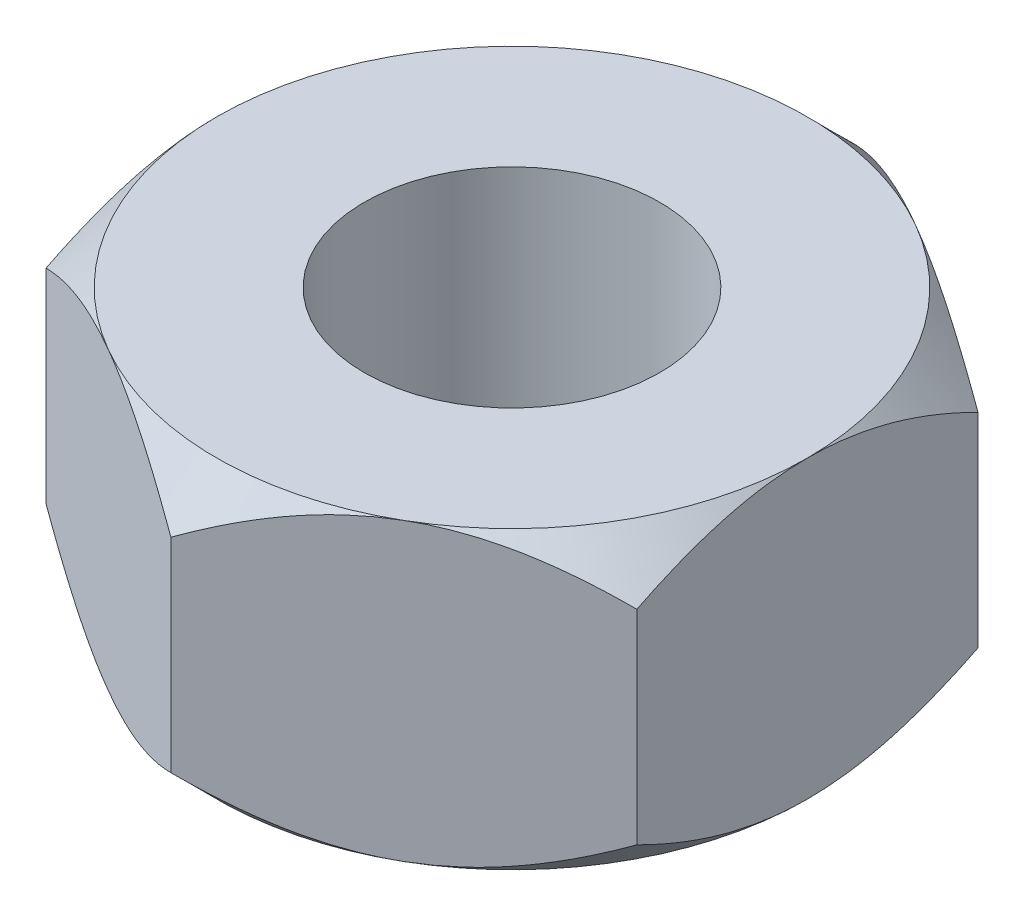
SolidWorks part; units mm, degrees
material "Plain Carbon Steel"
ref_plane "Front Plane" through (0, 0, 0) normal (0, 0, 1) x (1, 0, 0)
ref_plane "Top Plane" through (0, 0, 0) normal (0, 1, 0) x (1, 0, 0)
ref_plane "Right Plane" through (0, 0, 0) normal (1, 0, 0) x (0, 0, -1)
sketch "Sketch1" plane through (0, 0, 0) normal (0, 1, 0) x (1, 0, 0)
  line L1 (0, 4.6188) -> (-4, 2.3094)
  line L2 (-4, 2.3094) -> (-4, -2.3094)
  line L3 (-4, -2.3094) -> (0, -4.6188)
  line L4 (0, -4.6188) -> (4, -2.3094)
  line L5 (4, -2.3094) -> (4, 2.3094)
  line L6 (4, 2.3094) -> (0, 4.6188)
  circle A0 centre (0, 0) radius 2
  circle A1 centre (0, 0) radius 4 construction
  dimension "D1" = 4
  dimension "D2" = 8
extrude "Boss-Extrude1" add sketch "Sketch1" along normal mid plane 4
sketch "Sketch2" plane through (0, 2, 0) normal (0, 1, 0) x (1, 0, 0)
  line L0 (-4, 2.3094) -> (-4, -2.3094) construction
  circle A0 centre (0, 0) radius 4
sketch "Sketch3" plane through (0, 0, 0) normal (0, 0, 1) x (1, 0, 0)
  line L0 (-4.65, 1.35) -> (-4, 2)
  line L3 (-4, 2) -> (-4.65, 2)
  line L4 (-4.65, 2) -> (-4.65, 1.35)
  dimension "D1" = 0.65
  dimension "D2" = 0.65
sweep "Cut-Sweep1" cut profiles "Sketch3" path "Sketch2"
mirror "Mirror1" about plane through (0, 0, 0) normal (0, 1, 0) of "Cut-Sweep1"
